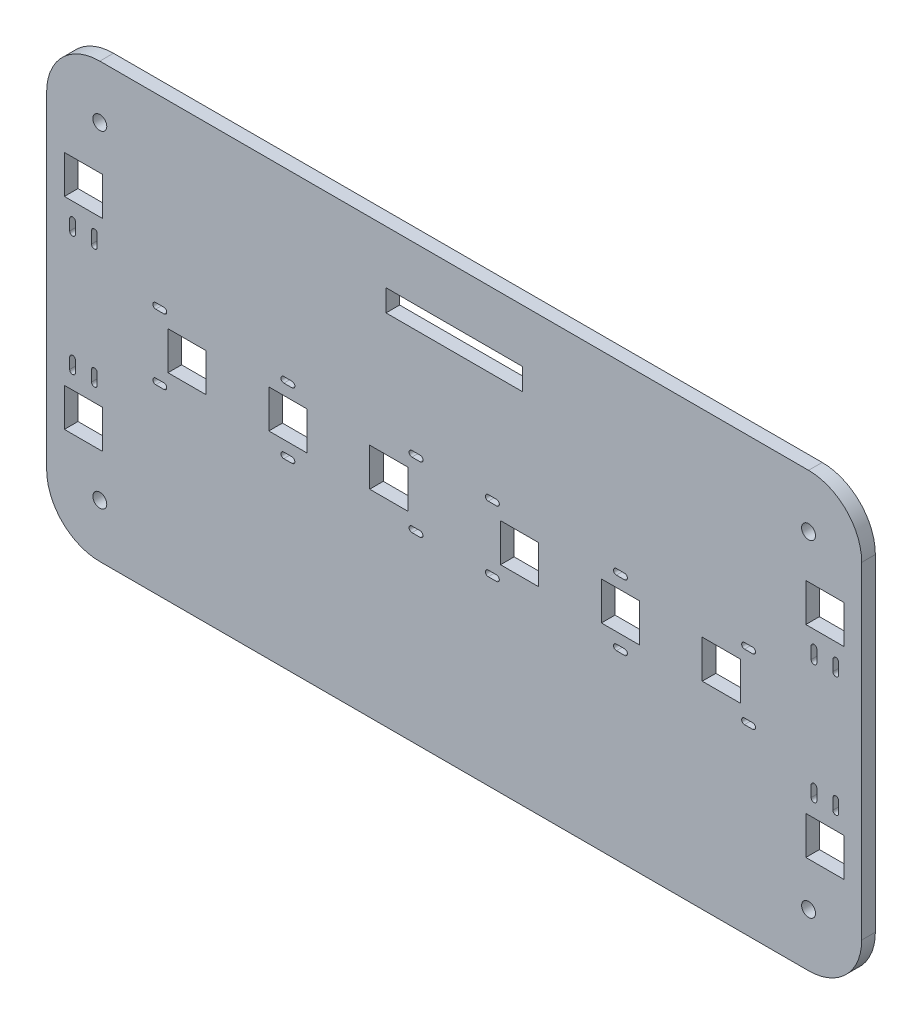
SolidWorks part; units mm, degrees
material "PMMA"
ref_plane "前视基准面" through (0, 0, 0) normal (0, 0, 1) x (1, 0, 0)
ref_plane "上视基准面" through (0, 0, 0) normal (0, 1, 0) x (1, 0, 0)
ref_plane "右视基准面" through (0, 0, 0) normal (1, 0, 0) x (0, 0, -1)
sketch "草图2" plane through (0, 0, 0) normal (0, 0, 1) x (1, 0, 0)
  line L0 (0, 1004.6496) -> (0, 0) construction
  line L10 (-68, -43) -> (-68, -57)
  line L11 (-31, -43) -> (-17, -43)
  line L19 (-22.1829, -50) -> (7.7078, -50) construction
  line L24 (31, -57) -> (17, -57)
  line L29 (17, -43) -> (17, -57)
  line L46 (129, -80) -> (143, -80)
  line L47 (-130, -130) -> (130, -130) construction
  line L48 (-150, -110) -> (-150, 10) construction
  line L49 (-130, 30) -> (130, 30) construction
  line L50 (150, -110) -> (150, 10) construction
  line L51 (0, 30) -> (0, 0) construction
  line L52 (-150, -50) -> (150, -50) construction
  line L53 (129, -6) -> (143, -6)
  line L58 (129, -6) -> (129, -20)
  line L59 (129, -20) -> (143, -20)
  line L60 (143, -6) -> (143, -20)
  line L65 (28.2222, 0) -> (37.5982, 0) construction
  line L66 (0, 0) -> (0, -130) construction
  line L71 (-130, 29.5) -> (130, 29.5)
  line L72 (-25, 10) -> (25, 10)
  line L73 (0, 0) -> (0, -1009.2088) construction
  line L74 (136, -20) -> (136, -6) construction
  line L75 (129, -13) -> (143, -13) construction
  line L76 (143, -94) -> (143, -80)
  line L77 (129, -94) -> (143, -94)
  line L78 (129, -94) -> (129, -80)
  line L79 (-129, -94) -> (-129, -80)
  line L80 (-129, -94) -> (-143, -94)
  line L81 (-143, -94) -> (-143, -80)
  line L82 (-129, -80) -> (-143, -80)
  line L83 (-129, -20) -> (-143, -20)
  line L84 (-143, -6) -> (-143, -20)
  line L85 (-129, -6) -> (-143, -6)
  line L86 (-129, -6) -> (-129, -20)
  line L87 (-31, -43) -> (-31, -57)
  line L88 (-31, -57) -> (-17, -57)
  line L89 (-17, -43) -> (-17, -57)
  line L90 (-24, -57) -> (-24, -43) construction
  line L91 (-31, -50) -> (-17, -50) construction
  line L92 (-68, -43) -> (-54, -43)
  line L93 (-54, -43) -> (-54, -57)
  line L94 (-68, -57) -> (-54, -57)
  line L95 (-105, -43) -> (-105, -57)
  line L96 (-105, -43) -> (-91, -43)
  line L97 (-91, -43) -> (-91, -57)
  line L98 (-105, -57) -> (-91, -57)
  line L99 (31, -43) -> (17, -43)
  line L100 (31, -43) -> (31, -57)
  line L101 (68, -43) -> (54, -43)
  line L102 (54, -43) -> (54, -57)
  line L103 (68, -57) -> (54, -57)
  line L104 (68, -43) -> (68, -57)
  line L105 (105, -43) -> (91, -43)
  line L106 (91, -43) -> (91, -57)
  line L107 (105, -57) -> (91, -57)
  line L108 (105, -43) -> (105, -57)
  line L109 (-31, -43) -> (-68, -43) construction
  line L110 (-61, -43) -> (-61, -57) construction
  line L112 (-111, -35) -> (-11, -35) construction
  line L113 (-111, -35) -> (-111, -65) construction
  line L114 (-111, -65) -> (-11, -65) construction
  line L115 (-11, -35) -> (-11, -65) construction
  line L116 (-61, -65) -> (-61, -35) construction
  line L117 (-111, -50) -> (-11, -50) construction
  line L121 (-108, -38) -> (-14, -38) construction
  line L122 (-14, -38) -> (-14, -62) construction
  line L123 (-108, -62) -> (-14, -62) construction
  line L124 (-108, -38) -> (-108, -62) construction
  line L125 (136, -20) -> (136, -42.3074) construction
  line L126 (-25, 10) -> (-25, 2)
  line L127 (128, -4) -> (144, -4) construction
  line L128 (128, -4) -> (128, -96) construction
  line L129 (128, -96) -> (144, -96) construction
  line L130 (144, -4) -> (144, -96) construction
  line L131 (136, -96) -> (136, -4) construction
  line L132 (128, -50) -> (144, -50) construction
  line L133 (132, -28) -> (140, -28) construction
  line L134 (132, -28) -> (132, -72) construction
  line L135 (132, -72) -> (140, -72) construction
  line L136 (140, -28) -> (140, -72) construction
  line L137 (136, -72) -> (136, -28) construction
  line L138 (132, -50) -> (140, -50) construction
  line L139 (-25, 2) -> (25, 2)
  line L140 (25, 10) -> (25, 2)
  line L141 (0, 2) -> (0, 10) construction
  line L142 (-25, 6) -> (25, 6) construction
  line L143 (149.5, -110) -> (149.5, 10)
  line L144 (-130, -129.5) -> (130, -129.5)
  line L145 (-149.5, -110) -> (-149.5, 10)
  line L150 (132, -25.839) -> (132, -30.161) construction
  line L151 (133.05, -25.839) -> (133.05, -30.161)
  line L152 (130.95, -25.839) -> (130.95, -30.161)
  line L153 (140, -26) -> (140, -30) construction
  line L154 (141.05, -26) -> (141.05, -30)
  line L155 (138.95, -26) -> (138.95, -30)
  line L156 (132, -74) -> (132, -70) construction
  line L157 (130.95, -74) -> (130.95, -70)
  line L158 (133.05, -74) -> (133.05, -70)
  line L159 (140, -74) -> (140, -70) construction
  line L160 (138.95, -74) -> (138.95, -70)
  line L161 (141.05, -74) -> (141.05, -70)
  line L162 (-140, -26) -> (-140, -30) construction
  line L163 (-141.05, -26) -> (-141.05, -30)
  line L164 (-138.95, -26) -> (-138.95, -30)
  line L165 (-132, -25.839) -> (-132, -30.161) construction
  line L166 (-133.05, -25.839) -> (-133.05, -30.161)
  line L167 (-130.95, -25.839) -> (-130.95, -30.161)
  line L168 (-132, -74) -> (-132, -70) construction
  line L169 (-130.95, -74) -> (-130.95, -70)
  line L170 (-133.05, -74) -> (-133.05, -70)
  line L171 (-140, -74) -> (-140, -70) construction
  line L172 (-138.95, -74) -> (-138.95, -70)
  line L173 (-141.05, -74) -> (-141.05, -70)
  line L174 (-62.5, -38) -> (-59.5, -38) construction
  line L175 (-62.5, -36.95) -> (-59.5, -36.95)
  line L176 (-62.5, -39.05) -> (-59.5, -39.05)
  line L177 (-62.5, -62) -> (-59.5, -62) construction
  line L178 (-62.5, -60.95) -> (-59.5, -60.95)
  line L179 (-62.5, -63.05) -> (-59.5, -63.05)
  line L180 (-15.5, -62) -> (-12.5, -62) construction
  line L181 (-15.5, -60.95) -> (-12.5, -60.95)
  line L182 (-15.5, -63.05) -> (-12.5, -63.05)
  line L183 (-12.5, -38) -> (-15.5, -38) construction
  line L184 (-12.5, -39.05) -> (-15.5, -39.05)
  line L185 (-12.5, -36.95) -> (-15.5, -36.95)
  line L186 (-109.5, -38) -> (-106.5, -38) construction
  line L187 (-109.5, -36.95) -> (-106.5, -36.95)
  line L188 (-109.5, -39.05) -> (-106.5, -39.05)
  line L189 (-109.5, -62) -> (-106.5, -62) construction
  line L190 (-109.5, -60.95) -> (-106.5, -60.95)
  line L191 (-109.5, -63.05) -> (-106.5, -63.05)
  line L192 (109.5, -38) -> (106.5, -38) construction
  line L193 (109.5, -36.95) -> (106.5, -36.95)
  line L194 (109.5, -39.05) -> (106.5, -39.05)
  line L195 (109.5, -62) -> (106.5, -62) construction
  line L196 (109.5, -60.95) -> (106.5, -60.95)
  line L197 (109.5, -63.05) -> (106.5, -63.05)
  line L198 (62.5, -62) -> (59.5, -62) construction
  line L199 (62.5, -60.95) -> (59.5, -60.95)
  line L200 (62.5, -63.05) -> (59.5, -63.05)
  line L201 (15.5, -62) -> (12.5, -62) construction
  line L202 (15.5, -60.95) -> (12.5, -60.95)
  line L203 (15.5, -63.05) -> (12.5, -63.05)
  line L204 (62.5, -38) -> (59.5, -38) construction
  line L205 (62.5, -36.95) -> (59.5, -36.95)
  line L206 (62.5, -39.05) -> (59.5, -39.05)
  line L207 (12.5, -38) -> (15.5, -38) construction
  line L208 (12.5, -39.05) -> (15.5, -39.05)
  line L209 (12.5, -36.95) -> (15.5, -36.95)
  arc A0 (130, 30) -> (150, 10) centre (130, 10) cw construction
  arc A1 (150, -110) -> (130, -130) centre (130, -110) cw construction
  arc A2 (-130, -130) -> (-150, -110) centre (-130, -110) cw construction
  arc A3 (-150, 10) -> (-130, 30) centre (-130, 10) cw construction
  circle A5 centre (130, -110) radius 2.55
  circle A6 centre (130, 10) radius 2.55
  circle A7 centre (-130, -110) radius 2.55
  circle A8 centre (-130, 10) radius 2.55
  arc A33 (130, 29.5) -> (149.5, 10) centre (130, 10) cw
  arc A34 (149.5, -110) -> (130, -129.5) centre (130, -110) cw
  arc A35 (-130, -129.5) -> (-149.5, -110) centre (-130, -110) cw
  arc A36 (-149.5, 10) -> (-130, 29.5) centre (-130, 10) cw
  arc A41 (133.05, -25.839) -> (130.95, -25.839) centre (132, -25.839) ccw
  arc A42 (130.95, -30.161) -> (133.05, -30.161) centre (132, -30.161) ccw
  arc A43 (141.05, -26) -> (138.95, -26) centre (140, -26) ccw
  arc A44 (138.95, -30) -> (141.05, -30) centre (140, -30) ccw
  arc A45 (130.95, -74) -> (133.05, -74) centre (132, -74) ccw
  arc A46 (133.05, -70) -> (130.95, -70) centre (132, -70) ccw
  arc A47 (138.95, -74) -> (141.05, -74) centre (140, -74) ccw
  arc A48 (141.05, -70) -> (138.95, -70) centre (140, -70) ccw
  arc A49 (-141.05, -26) -> (-138.95, -26) centre (-140, -26) cw
  arc A50 (-138.95, -30) -> (-141.05, -30) centre (-140, -30) cw
  arc A51 (-133.05, -25.839) -> (-130.95, -25.839) centre (-132, -25.839) cw
  arc A52 (-130.95, -30.161) -> (-133.05, -30.161) centre (-132, -30.161) cw
  arc A53 (-130.95, -74) -> (-133.05, -74) centre (-132, -74) cw
  arc A54 (-133.05, -70) -> (-130.95, -70) centre (-132, -70) cw
  arc A55 (-138.95, -74) -> (-141.05, -74) centre (-140, -74) cw
  arc A56 (-141.05, -70) -> (-138.95, -70) centre (-140, -70) cw
  arc A57 (-62.5, -36.95) -> (-62.5, -39.05) centre (-62.5, -38) ccw
  arc A58 (-59.5, -39.05) -> (-59.5, -36.95) centre (-59.5, -38) ccw
  arc A59 (-62.5, -60.95) -> (-62.5, -63.05) centre (-62.5, -62) ccw
  arc A60 (-59.5, -63.05) -> (-59.5, -60.95) centre (-59.5, -62) ccw
  arc A61 (-15.5, -60.95) -> (-15.5, -63.05) centre (-15.5, -62) ccw
  arc A62 (-12.5, -63.05) -> (-12.5, -60.95) centre (-12.5, -62) ccw
  arc A63 (-12.5, -39.05) -> (-12.5, -36.95) centre (-12.5, -38) ccw
  arc A64 (-15.5, -36.95) -> (-15.5, -39.05) centre (-15.5, -38) ccw
  arc A65 (-109.5, -36.95) -> (-109.5, -39.05) centre (-109.5, -38) ccw
  arc A66 (-106.5, -39.05) -> (-106.5, -36.95) centre (-106.5, -38) ccw
  arc A67 (-109.5, -60.95) -> (-109.5, -63.05) centre (-109.5, -62) ccw
  arc A68 (-106.5, -63.05) -> (-106.5, -60.95) centre (-106.5, -62) ccw
  arc A69 (109.5, -36.95) -> (109.5, -39.05) centre (109.5, -38) cw
  arc A70 (106.5, -39.05) -> (106.5, -36.95) centre (106.5, -38) cw
  arc A71 (109.5, -60.95) -> (109.5, -63.05) centre (109.5, -62) cw
  arc A72 (106.5, -63.05) -> (106.5, -60.95) centre (106.5, -62) cw
  arc A73 (62.5, -60.95) -> (62.5, -63.05) centre (62.5, -62) cw
  arc A74 (59.5, -63.05) -> (59.5, -60.95) centre (59.5, -62) cw
  arc A75 (15.5, -60.95) -> (15.5, -63.05) centre (15.5, -62) cw
  arc A76 (12.5, -63.05) -> (12.5, -60.95) centre (12.5, -62) cw
  arc A77 (62.5, -36.95) -> (62.5, -39.05) centre (62.5, -38) cw
  arc A78 (59.5, -39.05) -> (59.5, -36.95) centre (59.5, -38) cw
  arc A79 (12.5, -39.05) -> (12.5, -36.95) centre (12.5, -38) cw
  arc A80 (15.5, -36.95) -> (15.5, -39.05) centre (15.5, -38) cw
  point P0 (0, 0)
  point P1 (0, 0)
  point P4 (-24, -50)
  point P36 (-61, -50)
  point P38 (0, -50)
  point P39 (-61, -50)
  point P40 (0, -50)
  point P41 (136, -13)
  point P51 (136, -50)
  point P53 (136, -50)
  point P54 (136, -50)
  point P61 (150, 30)
  point P64 (150, -130)
  point P70 (-150, 30)
  point P99 (-61, -38)
  point P102 (-61, -38)
  point P103 (-61, -62)
  point P107 (-61, -62)
  point P110 (108, -38)
  point P117 (108, -62)
  point P126 (-140, -28)
  point P141 (-14, -62)
  point P145 (0, 6)
  point P154 (132, -28)
  point P161 (140, -28)
  point P168 (132, -72)
  point P175 (140, -72)
  point P188 (-132, -28)
  point P195 (-132, -72)
  point P202 (-140, -72)
  point P207 (-14, -38)
  point P219 (-108, -38)
  point P226 (-108, -62)
  point P236 (61, -62)
  point P243 (14, -62)
  point P250 (61, -38)
  point P257 (14, -38)
  dimension "D15" = 20
  dimension "D16" = 5.1
  dimension "D17" = 5.1
  dimension "D18" = 5.1
  dimension "D19" = 5.1
  dimension "D20" = 30
  dimension "D25" = 1.05
  dimension "D26" = 1.05
  dimension "D27" = 1.05
  dimension "D28" = 1.05
  dimension "D29" = 1.05
  dimension "D30" = 1.05
  dimension "D35" = 1.05
  dimension "D36" = 4.322
  dimension "D37" = 1.05
  dimension "D38" = 4
  dimension "D41" = 1.05
  dimension "D43" = 1.05
  dimension "D3" = 14
  dimension "D4" = 14
  dimension "D5" = 17
  dimension "D6" = 50
  dimension "D7" = 8
  dimension "D8" = 3
  dimension "D9" = 37
  dimension "D10" = 300
  dimension "D11" = 160
  dimension "D12" = 14
  dimension "D13" = 14
  dimension "D14" = 7
  dimension "D21" = 100
  dimension "D22" = 50
  dimension "D23" = 30
  dimension "D24" = 3
  dimension "D31" = 92
  dimension "D32" = 16
  dimension "D33" = 8
  dimension "D34" = 44
  dimension "D39" = 2
  dimension "D42" = 4
  dimension "D44" = 4
  dimension "D45" = 3
  dimension "D46" = 3
  dimension "D47" = 3
  dimension "D48" = 3
  dimension "D49" = 3
  dimension "D50" = 3
  dimension "D40" = 0.5
extrude "凸台-拉伸1" add sketch "草图2" along normal blind 5
